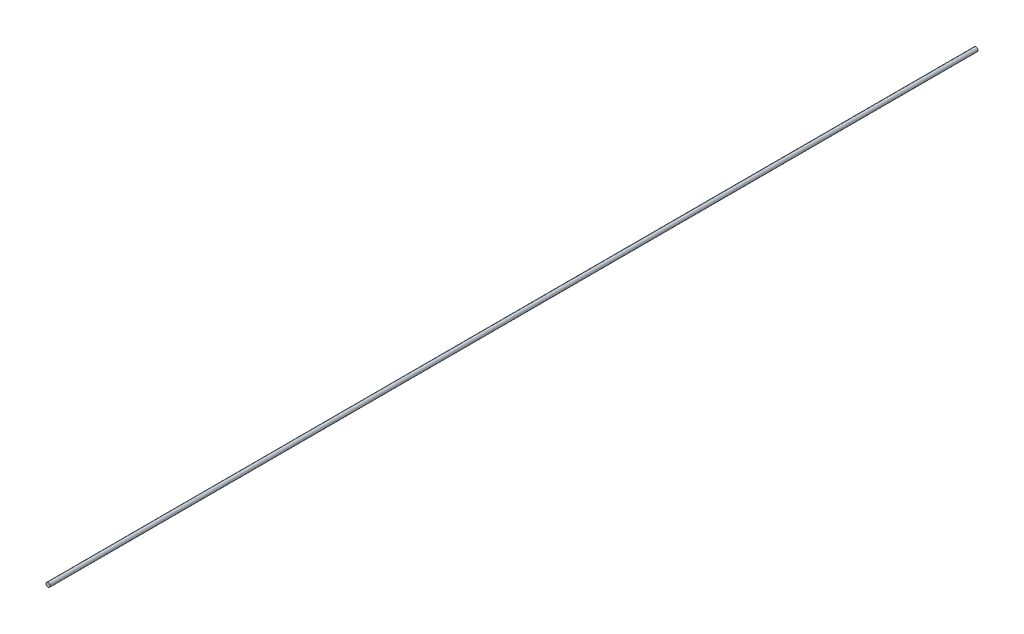
SolidWorks part; units mm, degrees
ref_plane "Front Plane" through (0, 0, 0) normal (0, 0, 1) x (1, 0, 0)
ref_plane "Top Plane" through (0, 0, 0) normal (0, 1, 0) x (1, 0, 0)
ref_plane "Right Plane" through (0, 0, 0) normal (1, 0, 0) x (0, 0, -1)
sketch "Sketch1" plane through (0, 0, 0) normal (0, 0, 1) x (1, 0, 0)
  circle A0 centre (0, 0) radius 2
  dimension "D1" = 4
extrude "Boss-Extrude1" add sketch "Sketch1" along normal blind 900
